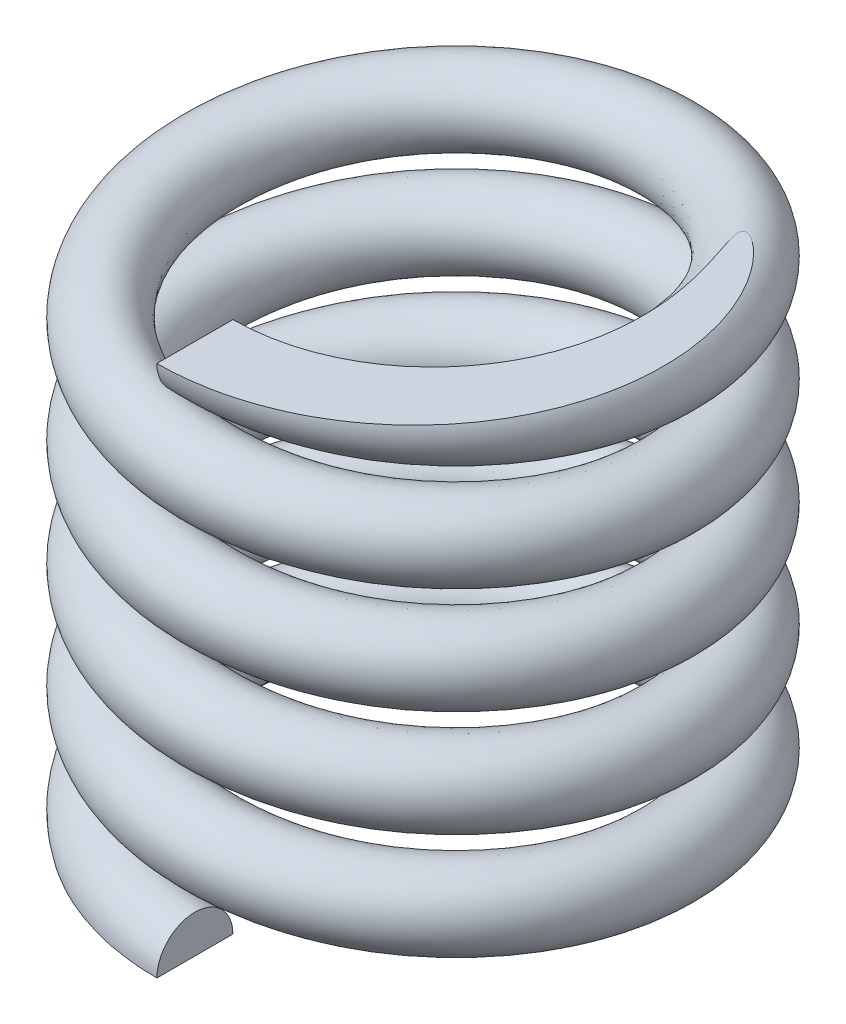
SolidWorks part; units mm, degrees
ref_plane "Front Plane" through (0, 0, 0) normal (0, 0, 1) x (1, 0, 0)
ref_plane "Top Plane" through (0, 0, 0) normal (0, 1, 0) x (1, 0, 0)
ref_plane "Right Plane" through (0, 0, 0) normal (1, 0, 0) x (0, 0, -1)
sketch "Sketch1" plane through (0, 0, 0) normal (0, 1, 0) x (1, 0, 0)
  circle A0 centre (0, 0) radius 3
  dimension "D1" = 6
curve "Helix/Spiral1" pitch 1.4 height 7 turns 5
sketch "Sketch2" plane through (0, 0, 0) normal (1, 0, 0) x (0, 0, -1)
  circle A0 centre (-3, 0) radius 0.5
  spline S0 degree 3 poles (-3, 0) (-3, 0.029) (-2.8438, 0.0876) (-2.1765, 0.175) (-1.1779, 0.2625) (0, 0.35) (1.1779, 0.4375) (2.1765, 0.525) (2.8438, 0.6125) (3.0781, 0.7) (2.8438, 0.7875) (2.1765, 0.875) (0.8451, 0.9917) (-0.8451, 1.1083) (-2.1765, 1.225) (-2.8438, 1.3125) (-3.0781, 1.4) (-2.8438, 1.4875) (-2.1765, 1.575) (-0.8451, 1.6917) (0.8451, 1.8083) (2.1765, 1.925) (2.8438, 2.0125) (3.0781, 2.1) (2.8438, 2.1875) (2.1765, 2.275) (0.8451, 2.3917) (-0.8451, 2.5083) (-2.1765, 2.625) (-2.8438, 2.7125) (-3.0781, 2.8) (-2.8438, 2.8875) (-2.1765, 2.975) (-0.8451, 3.0917) (0.8451, 3.2083) (2.1765, 3.325) (2.8438, 3.4125) (3.0781, 3.5) (2.8438, 3.5875) (2.1765, 3.675) (0.8451, 3.7917) (-0.8451, 3.9083) (-2.1765, 4.025) (-2.8438, 4.1125) (-3.0781, 4.2) (-2.8438, 4.2875) (-2.1765, 4.375) (-0.8451, 4.4917) (0.8451, 4.6083) (2.1765, 4.725) (2.8438, 4.8125) (3.0781, 4.9) (2.8438, 4.9875) (2.1765, 5.075) (0.8451, 5.1917) (-0.8451, 5.3083) (-2.1765, 5.425) (-2.8438, 5.5125) (-3.0781, 5.6) (-2.8438, 5.6875) (-2.1765, 5.775) (-0.8451, 5.8917) (0.8451, 6.0083) (2.1765, 6.125) (2.8438, 6.2125) (3.0781, 6.3) (2.8438, 6.3875) (2.1765, 6.475) (1.1779, 6.5625) (0, 6.65) (-1.1779, 6.7375) (-2.1765, 6.825) (-2.8438, 6.9124) (-3, 6.971) (-3, 7) knots 0 0 0 0 0.0125 0.025 0.0375 0.05 0.0625 0.075 0.0875 0.1 0.1125 0.125 0.1375 0.1625 0.175 0.1875 0.2 0.2125 0.225 0.2375 0.2625 0.275 0.2875 0.3 0.3125 0.325 0.3375 0.3625 0.375 0.3875 0.4 0.4125 0.425 0.4375 0.4625 0.475 0.4875 0.5 0.5125 0.525 0.5375 0.5625 0.575 0.5875 0.6 0.6125 0.625 0.6375 0.6625 0.675 0.6875 0.7 0.7125 0.725 0.7375 0.7625 0.775 0.7875 0.8 0.8125 0.825 0.8375 0.8625 0.875 0.8875 0.9 0.9125 0.925 0.9375 0.95 0.9625 0.975 0.9875 1 1 1 1 construction
  dimension "D1" = 1
sweep "Sweep1" add profiles "Sketch2" path "Helix/Spiral1"
sketch "Sketch3" plane through (0, 0, 0) normal (1, 0, 0) x (0, 0, -1)
  line L0 (5.2653, 3.5) -> (-4.5645, 3.5) construction
  line L1 (-3.7959, 0) -> (4.4183, 0)
  line L2 (-3.7959, 0) -> (-3.7959, -0.5)
  line L3 (-3.7959, -0.5) -> (4.4183, -0.5)
  line L4 (4.4183, 0) -> (4.4183, -0.5)
  line L5 (-3.7959, 7) -> (-3.7959, 7.5)
  line L6 (4.4183, 7) -> (4.4183, 7.5)
  line L7 (-3.7959, 7.5) -> (4.4183, 7.5)
  line L8 (-3.7959, 7) -> (4.4183, 7)
  dimension "D1" = 0.5
  dimension "D2" = 3.5
extrude "Cut-Extrude1" cut sketch "Sketch3" against normal mid plane 10
